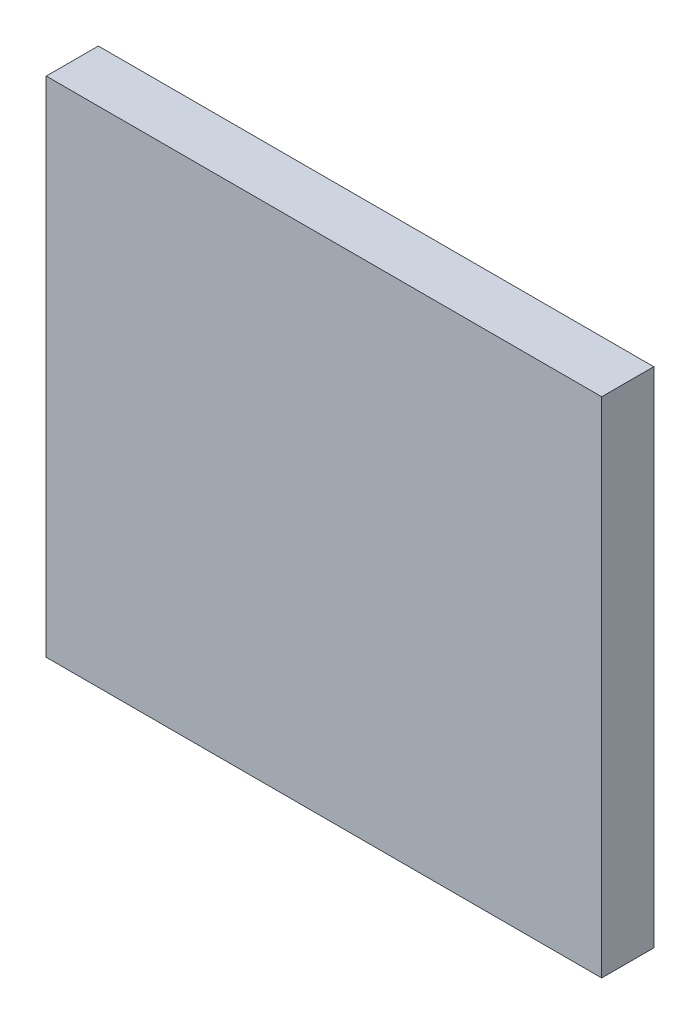
SolidWorks part; units mm, degrees
ref_plane "Front Plane" through (0, 0, 0) normal (0, 0, 1) x (1, 0, 0)
ref_plane "Top Plane" through (0, 0, 0) normal (0, 1, 0) x (1, 0, 0)
ref_plane "Right Plane" through (0, 0, 0) normal (1, 0, 0) x (0, 0, -1)
sketch "Sketch1" plane through (0, 0, 0) normal (0, 0, 1) x (1, 0, 0)
  line L1 (0, 0) -> (50.8, 0)
  line L2 (0, 0) -> (0, 46.0375)
  line L3 (0, 46.0375) -> (50.8, 46.0375)
  line L4 (50.8, 0) -> (50.8, 46.0375)
  dimension "D1" = 50.8
  dimension "D2" = 46.0375
extrude "Boss-Extrude1" add sketch "Sketch1" along normal blind 4.7625
